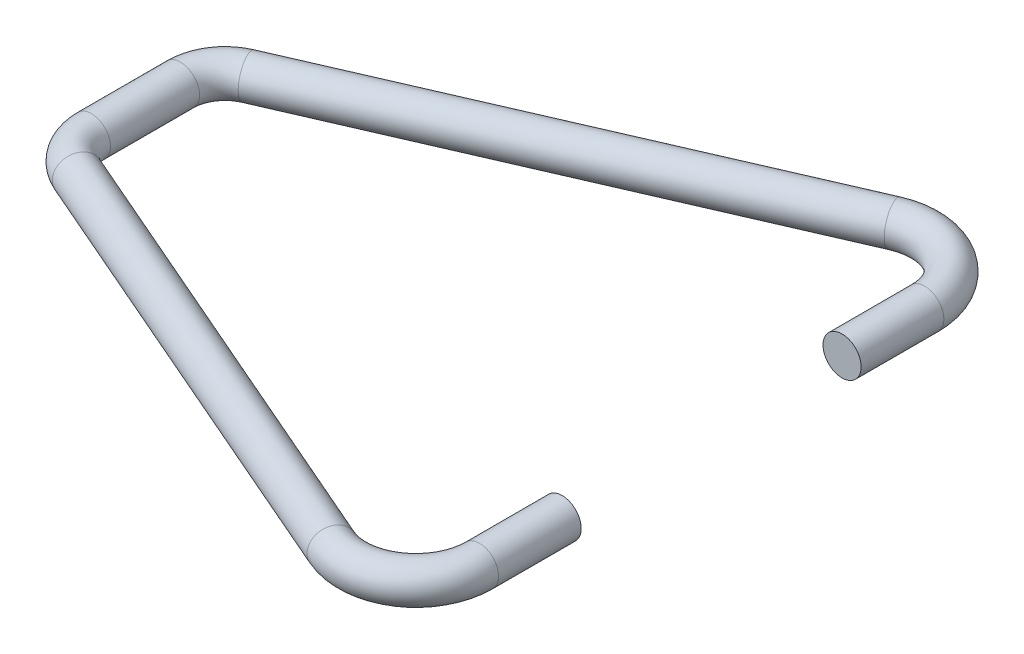
SolidWorks part; units mm, degrees
ref_plane "Alzado" through (0, 0, 0) normal (0, 0, 1) x (1, 0, 0)
ref_plane "Planta" through (0, 0, 0) normal (0, 1, 0) x (1, 0, 0)
ref_plane "Vista lateral" through (0, 0, 0) normal (1, 0, 0) x (0, 0, -1)
sketch "Croquis1" plane through (0, 0, 0) normal (0, 1, 0) x (1, 0, 0)
  line L0 (0, 0) -> (0, 7)
  line L1 (4.2114, 13.4206) -> (75.0163, 44.1723)
  line L2 (89, 35) -> (89, 22)
  line L3 (4.2114, 13.4206) -> (41.6807, 13.4206) construction
  arc A0 (0, 7) -> (4.2114, 13.4206) centre (7, 7) cw
  arc A1 (75.0163, 44.1723) -> (89, 35) centre (79, 35) cw
  dimension "D5" = 10
  dimension "D6" = 7
  dimension "D1" = 89
  dimension "D2" = 7
  dimension "D3" = 13
  dimension "D4" = 35
sketch "Croquis2" plane through (0, 0, 0) normal (0, 0, 1) x (1, 0, 0)
  circle A0 centre (0, 0) radius 3
  dimension "D1" = 6
sweep "Barrer1" add profiles "Croquis2" path "Croquis1"
ref_plane "Plano1" through (0, 0, 0) normal (0, 0, 1) x (1, 0, 0)
mirror "Simetría1" about plane through (0, 0, 0) normal (0, 0, 1) of "Barrer1"
